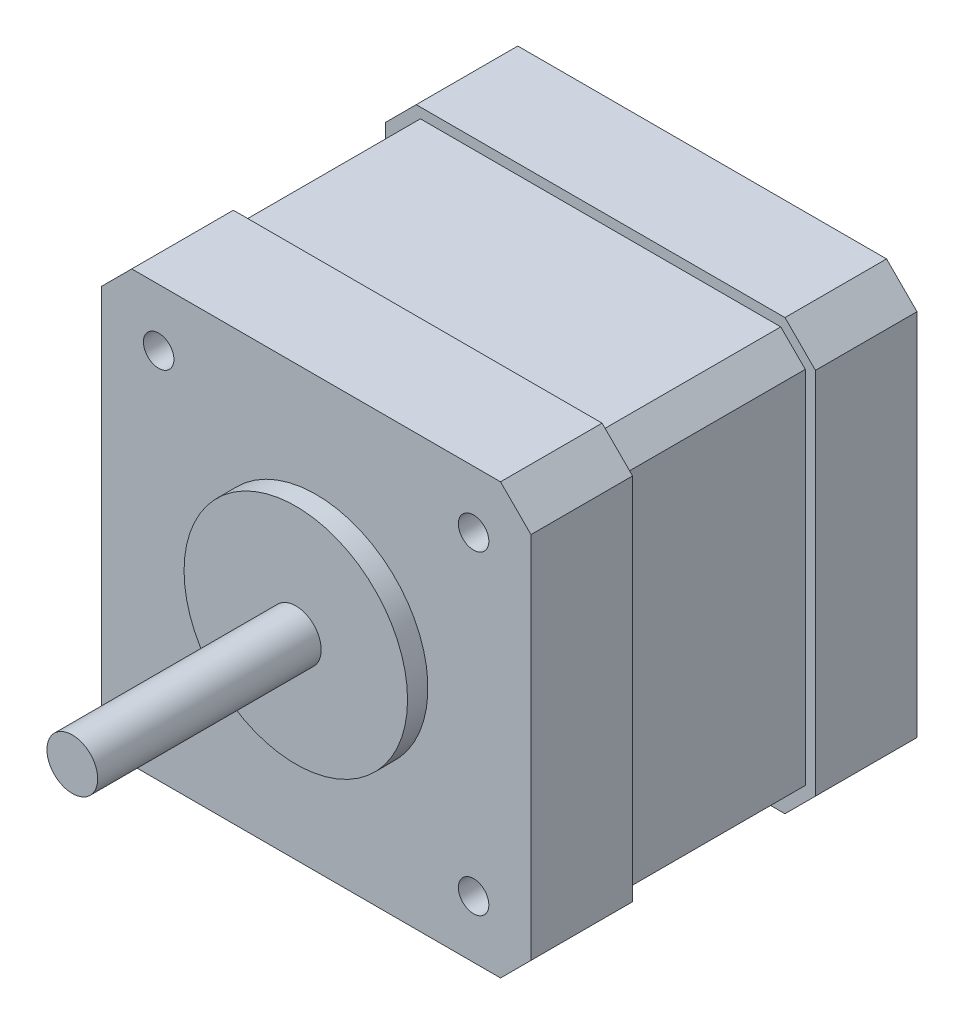
SolidWorks part; units mm, degrees
ref_plane "Спереди" through (0, 0, 0) normal (0, 0, 1) x (1, 0, 0)
ref_plane "Сверху" through (0, 0, 0) normal (0, 1, 0) x (1, 0, 0)
ref_plane "Справа" through (0, 0, 0) normal (1, 0, 0) x (0, 0, -1)
sketch "Эскиз1" plane through (0, 0, 0) normal (0, 0, 1) x (1, 0, 0)
  line L0 (-32.7678, -16.5362) -> (-32.7678, 19.7638)
  line L1 (-29.7678, 22.7638) -> (6.5322, 22.7638)
  line L2 (9.5322, 19.7638) -> (9.5322, -16.5362)
  line L3 (6.5322, -19.5362) -> (-29.7678, -19.5362)
  line L4 (-32.7678, 19.7638) -> (-29.7678, 22.7638)
  line L5 (6.5322, 22.7638) -> (9.5322, 19.7638)
  line L6 (9.5322, -16.5362) -> (6.5322, -19.5362)
  line L7 (-29.7678, -19.5362) -> (-32.7678, -16.5362)
  point P0 (-32.7678, -19.5362)
  point P1 (-32.7678, 22.7638)
  point P2 (9.5322, 22.7638)
  point P3 (9.5322, -19.5362)
extrude "Бобышка-Вытянуть1" add sketch "Эскиз1" along normal blind 10
sketch "Эскиз2" plane through (0, 0, 10) normal (0, 0, 1) x (1, 0, 0)
  circle A0 centre (-11.6178, 1.6138) radius 11
  dimension "D1" = 22
extrude "Бобышка-Вытянуть2" add sketch "Эскиз2" along normal blind 2
sketch "Эскиз3" plane through (0, 0, 12) normal (0, 0, 1) x (1, 0, 0)
  circle A0 centre (-11.6178, 1.6138) radius 2.5
extrude "Бобышка-Вытянуть3" add sketch "Эскиз3" along normal blind 22
sketch "Эскиз6" plane through (0, 0, 0) normal (0, 0, -1) x (-1, 0, 0)
  line L2 (11.6178, 21.7638) -> (-6.118, 21.7638)
  line L4 (-8.5322, 19.3496) -> (-8.5322, -16.122)
  line L5 (-6.5322, -19.5362) -> (-9.5322, -16.5362) construction
  line L6 (-6.118, -18.5362) -> (29.3535, -18.5362)
  line L7 (32.7678, -16.5362) -> (29.7678, -19.5362) construction
  line L9 (31.7678, -16.122) -> (31.7678, 19.3496)
  line L10 (29.7678, 22.7638) -> (32.7678, 19.7638) construction
  line L11 (11.6178, 21.7638) -> (29.3535, 21.7638)
  line L12 (-8.5322, -16.122) -> (-6.118, -18.5362)
  line L13 (-8.5322, 19.3496) -> (-6.118, 21.7638)
  line L14 (-9.5322, 19.7638) -> (-6.5322, 22.7638) construction
  line L15 (29.3535, 21.7638) -> (31.7678, 19.3496)
  line L16 (29.3535, -18.5362) -> (31.7678, -16.122)
  dimension "D1" = 1
  dimension "D2" = 1
  dimension "D3" = 1
  dimension "D4" = 1
extrude "Бобышка-Вытянуть4" add sketch "Эскиз6" along normal blind 18
sketch "Эскиз7" plane through (0, 0, -18) normal (0, 0, 1) x (1, 0, 0)
  line L0 (-32.7678, -16.5362) -> (-32.7678, 19.7638)
  line L1 (-29.7678, 22.7638) -> (6.5322, 22.7638)
  line L2 (9.5322, 19.7638) -> (9.5322, -16.5362)
  line L3 (6.5322, -19.5362) -> (-29.7678, -19.5362)
  line L4 (-32.7678, 19.7638) -> (-29.7678, 22.7638)
  line L5 (6.5322, 22.7638) -> (9.5322, 19.7638)
  line L6 (9.5322, -16.5362) -> (6.5322, -19.5362)
  line L7 (-29.7678, -19.5362) -> (-32.7678, -16.5362)
  point P0 (-32.7678, -19.5362)
  point P1 (-32.7678, 22.7638)
  point P2 (9.5322, 22.7638)
  point P3 (9.5322, -19.5362)
extrude "Бобышка-Вытянуть5" add sketch "Эскиз7" against normal blind 10
sketch "Эскиз4" plane through (0, 0, 10) normal (0, 0, 1) x (1, 0, 0)
  circle A0 centre (-27.1178, 17.1138) radius 1.5
  circle A1 centre (3.8822, 17.1138) radius 1.5
  circle A2 centre (3.8822, -13.8862) radius 1.5
  circle A3 centre (-27.1178, -13.8862) radius 1.5
  point P0 (3.8822, -13.8862)
  point P1 (-27.1178, -13.8862)
  point P14 (-27.1178, 17.1138)
  point P23 (3.8822, 17.1138)
  dimension "D1" = 31
  dimension "D2" = 31
extrude "Вырез-Вытянуть1" cut sketch "Эскиз4" against normal blind 46.5
sketch "Эскиз5" plane through (0, 0, -28) normal (0, 0, -1) x (-1, 0, 0)
  circle A0 centre (11.6178, 1.6138) radius 2.5
extrude "Вырез-Вытянуть2" cut sketch "Эскиз5" against normal blind 1
sketch "Sketch1" plane through (0, 0, 34) normal (0, 0, 1) x (1, 0, 0)
  point P0 (-11.6178, 1.6138)
